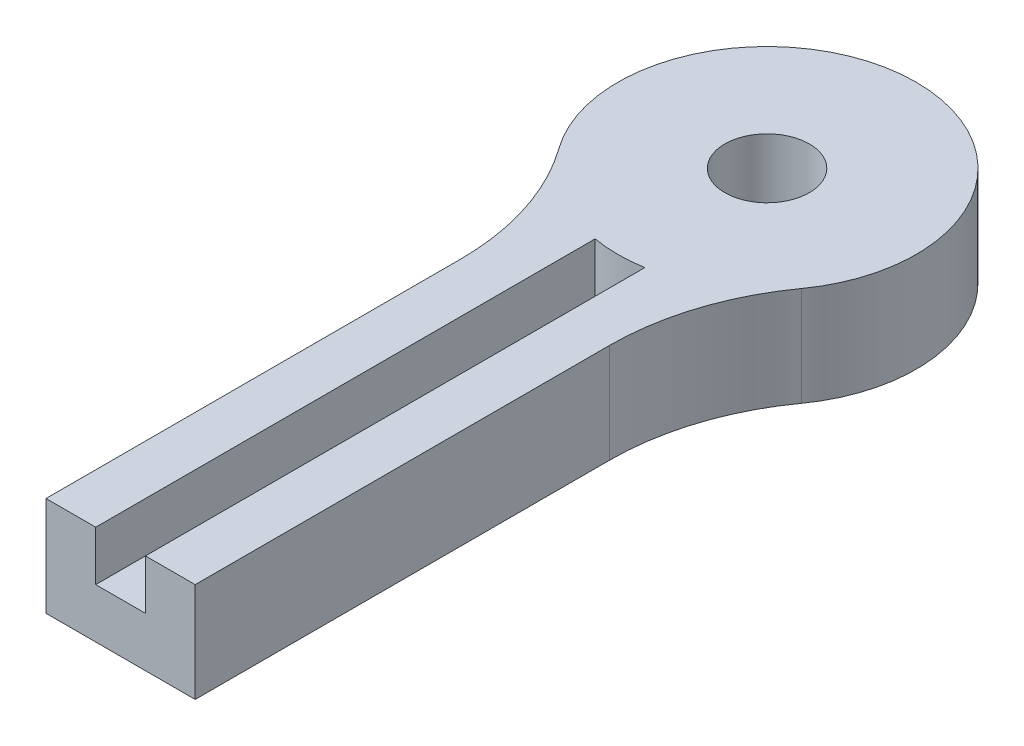
SolidWorks part; units mm, degrees
ref_plane "Front" through (0, 0, 0) normal (0, 0, 1) x (1, 0, 0)
ref_plane "Top" through (0, 0, 0) normal (0, 1, 0) x (1, 0, 0)
ref_plane "Right" through (0, 0, 0) normal (1, 0, 0) x (0, 0, -1)
sketch "Sketch1" plane through (0, 0, 0) normal (0, 1, 0) x (1, 0, 0)
  line L0 (0, -6) -> (0, -26)
  line L1 (-3, -26) -> (3, -26)
  line L2 (-3, -26) -> (-3, -5.1962)
  line L3 (3, -26) -> (3, -5.1962)
  circle A0 centre (0, 0) radius 1.7
  circle A1 centre (0, 0) radius 6
  point P9 (0, -26)
  dimension "D1" = 20
  dimension "D2" = 3.4
  dimension "D3" = 12
  dimension "D4" = 6
extrude "Boss-Extrude1" add sketch "Sketch1" along normal blind 2 contours A1 A0 | A1 L0 L1 L3 | A1 L2 L1 L0
sketch "Sketch2" plane through (0, 2, 0) normal (0, 1, 0) x (1, 0, 0)
  line L0 (-3, -26) -> (-3, -5.1962)
  line L1 (-3, -5.1962) -> (-1, -5.1962)
  line L2 (-1, -5.1962) -> (-1, -26)
  line L3 (-3, -26) -> (3, -26) construction
  line L4 (-1, -26) -> (-3, -26)
  line L5 (3, -26) -> (1, -26)
  line L6 (1, -26) -> (1, -5.1962)
  line L7 (1, -5.1962) -> (3, -5.1962)
  line L8 (3, -5.1962) -> (3, -26)
  dimension "D1" = 2
  dimension "D2" = 2
extrude "Boss-Extrude2" add sketch "Sketch2" along normal blind 2
sketch "Sketch3" plane through (0, 2, 0) normal (0, 1, 0) x (1, 0, 0)
  circle A0 centre (0, 0) radius 1.7
  circle A1 centre (0, 0) radius 6
extrude "Boss-Extrude3" add sketch "Sketch3" along normal blind 2
fillet "Fillet1" radius 10 2 edges at (3, 2, 5.1962) (-3, 2, 5.1962)
